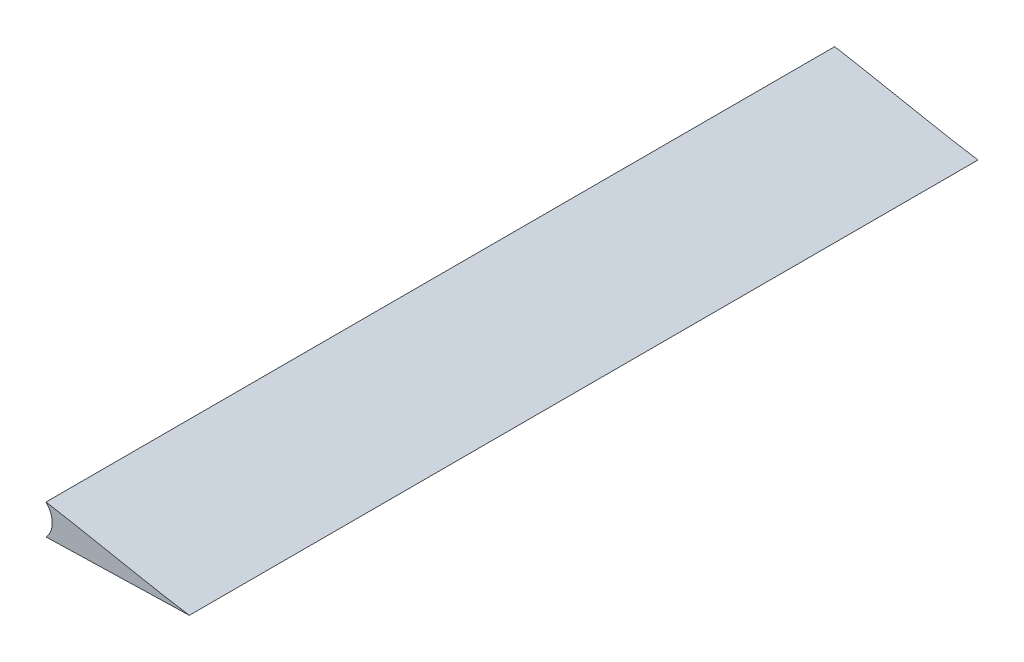
SolidWorks part; units mm, degrees
ref_plane "Front Plane" through (0, 0, 0) normal (0, 0, 1) x (1, 0, 0)
ref_plane "Top Plane" through (0, 0, 0) normal (0, 1, 0) x (1, 0, 0)
ref_plane "Right Plane" through (0, 0, 0) normal (1, 0, 0) x (0, 0, -1)
sketch "Sketch1" plane through (0, 0, 0) normal (0, 0, 1) x (1, 0, 0)
  spline S0 degree 3 poles (100.086, -5.734) (101.1259, -5.7095) (100.1039, -5.6235) (99.2806, -5.4646) (97.3018, -5.1673) (94.8938, -4.7403) (91.7634, -4.194) (88.0758, -3.5271) (83.8259, -2.7338) (79.0747, -1.8292) (73.8683, -0.8153) (68.2576, 0.2815) (62.2977, 1.4477) (56.0406, 2.6595) (49.5223, 3.8633) (42.7762, 5.0242) (35.8425, 6.1594) (28.7549, 7.2252) (21.5571, 8.212) (14.2899, 9.117) (6.9865, 9.8965) (-0.3123, 10.5674) (-7.5733, 11.1015) (-14.7568, 11.4845) (-21.8292, 11.7343) (-28.7564, 11.821) (-35.5035, 11.7506) (-42.0399, 11.5281) (-48.3376, 11.1397) (-54.3688, 10.5993) (-60.1078, 9.9161) (-65.5246, 9.0828) (-70.6007, 8.1336) (-75.3121, 7.0603) (-79.639, 5.8824) (-83.5658, 4.6206) (-87.0746, 3.2865) (-90.1553, 1.9084) (-92.7948, 0.5046) (-94.9831, -0.9044) (-96.7129, -2.2702) (-98.0005, -3.5808) (-98.7619, -4.7432) (-99.2301, -5.8582) (-98.606, -6.8701) (-97.4444, -7.5453) (-95.7467, -8.1886) (-93.4449, -8.653) (-90.5328, -8.9818) (-87.0128, -9.2499) (-82.9066, -9.4712) (-78.2402, -9.5911) (-73.0476, -9.7) (-67.3645, -9.7268) (-61.2329, -9.7356) (-54.6956, -9.664) (-47.7879, -9.5741) (-40.5477, -9.3999) (-33.0149, -9.2242) (-25.2415, -9.0244) (-17.2818, -8.802) (-9.1941, -8.5755) (-1.0348, -8.3896) (7.1349, -8.1639) (15.2619, -7.9372) (23.292, -7.7533) (31.172, -7.5204) (38.8533, -7.3203) (46.2827, -7.155) (53.3967, -6.9428) (60.1348, -6.7644) (66.4618, -6.6108) (72.37, -6.4441) (77.8517, -6.3047) (82.8703, -6.1895) (87.373, -6.0742) (91.2866, -5.9437) (94.6106, -5.8638) (97.1585, -5.8207) (99.2315, -5.7383) (100.086, -5.734) (101.1259, -5.7095) (100.1039, -5.6235) knots -0.008528 -0.003816 -0.00096 0 0.000951 0.003757 0.008317 0.014522 0.022293 0.03156 0.042221 0.054151 0.067231 0.081331 0.096307 0.112012 0.128327 0.145184 0.162488 0.180136 0.198033 0.216059 0.234134 0.252192 0.270104 0.287817 0.305235 0.322284 0.338896 0.354986 0.370506 0.385417 0.399632 0.413116 0.425823 0.437704 0.448737 0.45888 0.468105 0.476405 0.483748 0.490134 0.495557 0.500012 0.503516 0.506001 0.508215 0.511494 0.515844 0.521547 0.528755 0.537449 0.547575 0.559074 0.571867 0.585873 0.60098 0.61708 0.634081 0.651921 0.670484 0.689642 0.709259 0.729201 0.749303 0.769441 0.789466 0.809254 0.82867 0.847598 0.865915 0.883467 0.900079 0.915618 0.930135 0.943663 0.95605 0.967159 0.976853 0.984996 0.991472 0.996184 0.99904 1 1.000951 1.003757 1.008317 only from (100.9182, -5.7031) to (100.9182, -5.7031)
extrude "Boss-Extrude1" add sketch "Sketch1" along normal mid plane 1750
sketch "Sketch3" plane through (0, 0, 0) normal (0, 1, 0) x (1, 0, 0)
  line L0 (100.9182, 835.9) -> (44.3701, 835.9)
  line L2 (100.9182, 524.7075) -> (44.3701, 524.7075)
  line L3 (44.3701, 835.9) -> (44.3701, 524.7075)
  line L4 (100.9182, 875) -> (-99.0734, 875) construction
  line L5 (86.0245, 875) -> (86.5325, 875) construction
  line L8 (-6.5667, 0) -> (6.5667, 0) construction
  line L10 (100.9182, -524.7075) -> (44.3701, -524.7075)
  line L11 (44.3701, -835.9) -> (44.3701, -524.7075)
  line L12 (100.9182, -835.9) -> (44.3701, -835.9)
  line L13 (100.9182, 835.9) -> (100.9182, 941.2715)
  line L14 (100.9182, 941.2715) -> (-134.1332, 941.2715)
  line L15 (-134.1332, 941.2715) -> (-134.1332, -1428.4071)
  line L16 (-134.1332, -1428.4071) -> (100.9182, -1428.4071)
  line L17 (100.9182, -1428.4071) -> (100.9182, -835.9)
  line L18 (100.9182, -524.7075) -> (100.9182, 524.7075)
  dimension "D1" = 311.1925
  dimension "D2" = 56.5481
  dimension "D3" = 39.1
extrude "Cut-Extrude1" cut sketch "Sketch3" against normal through all both and the other way through all
delete or keep bodies "Body-Delete/Keep 1" type delete bodies bodies 102
sketch "Sketch4" plane through (0, 0, 835.9) normal (0, 0, 1) x (1, 0, 0)
  line L0 (44.3701, -7.194) -> (44.3701, 4.7454) construction
  line L1 (44.3701, 4.7454) -> (44.3701, -7.194)
  arc A0 (44.3701, 4.7454) -> (44.3701, -7.194) centre (38.4004, -1.2243) cw
  spline S0 degree 3 poles (44.3701, 4.7454) (46.112, 4.4494) (50.0329, 3.769) (56.0406, 2.6595) (62.2977, 1.4477) (68.2576, 0.2815) (73.8683, -0.8153) (79.0747, -1.8292) (83.8259, -2.7338) (88.0758, -3.5271) (91.7634, -4.194) (94.8938, -4.7403) (97.3018, -5.1673) (99.2806, -5.4646) (100.1039, -5.6235) (100.9179, -5.692) (100.9182, -5.7031) knots 0 0 0 0 0.013029 0.029344 0.045048 0.060025 0.074125 0.087205 0.099135 0.109796 0.119063 0.126834 0.133039 0.137599 0.140405 0.141356 0.141356 0.141356 0.141356 construction
extrude "Cut-Extrude2" cut sketch "Sketch4" against normal through all
